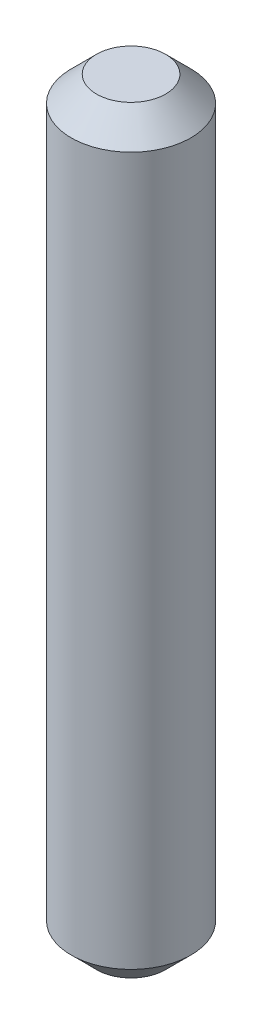
SolidWorks part; units mm, degrees
material "AISI Type 316L stainless steel"
ref_plane "Front Plane" through (0, 0, 0) normal (0, 0, 1) x (1, 0, 0)
ref_plane "Top Plane" through (0, 0, 0) normal (0, 1, 0) x (1, 0, 0)
ref_plane "Right Plane" through (0, 0, 0) normal (1, 0, 0) x (0, 0, -1)
sketch "Sketch1" plane through (0, 0, 0) normal (0, 0, 1) x (1, 0, 0)
  line L0 (0, 0) -> (0, 11.43)
  line L1 (0, 11.43) -> (0.5207, 11.43)
  line L2 (0.5207, 11.43) -> (0.9017, 11.049)
  line L3 (0.9017, 11.049) -> (0.9017, 0.381)
  line L4 (0.9017, 0.381) -> (0.5207, 0)
  line L5 (0.5207, 0) -> (0, 0)
  dimension "D1" = 0.9017
  dimension "D2" = 11.43
  dimension "D3" = 0.381
revolve "Revolve1" add sketch "Sketch1" angle 360 about L0
